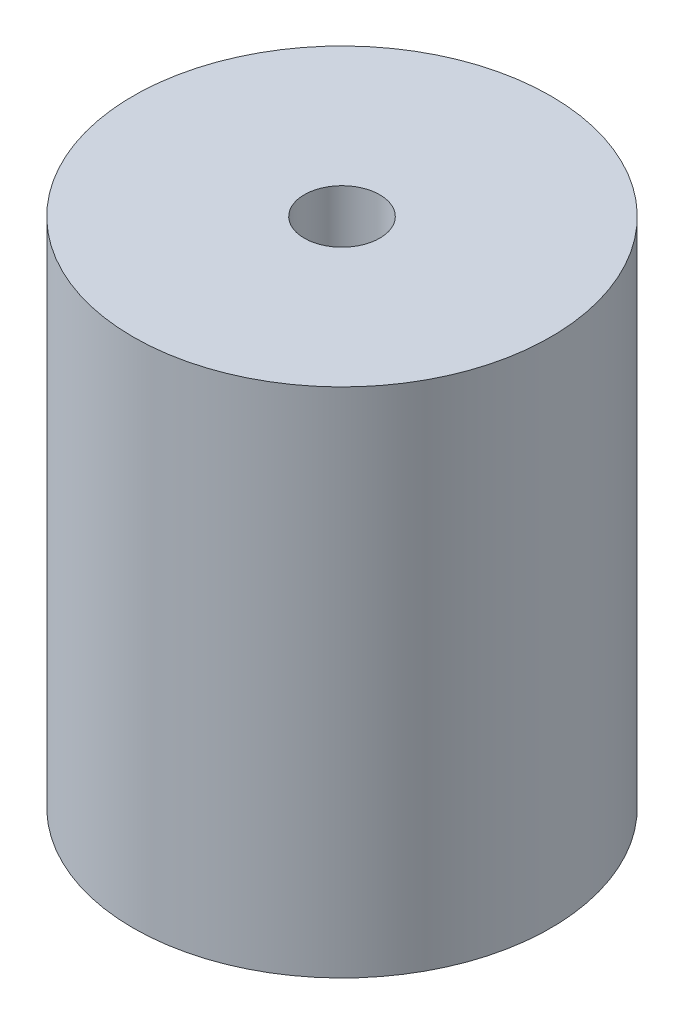
SolidWorks part; units mm, degrees
ref_plane "前视基准面" through (0, 0, 0) normal (0, 0, 1) x (1, 0, 0)
ref_plane "上视基准面" through (0, 0, 0) normal (0, 1, 0) x (1, 0, 0)
ref_plane "右视基准面" through (0, 0, 0) normal (1, 0, 0) x (0, 0, -1)
sketch "草图1" plane through (0, 0, 0) normal (0, 1, 0) x (1, 0, 0)
  circle A0 centre (0, 0) radius 7.75
  circle A1 centre (0, 0) radius 1.4
  dimension "D1" = 15.5
  dimension "D2" = 2.8
extrude "凸台-拉伸1" add sketch "草图1" along normal blind 19
